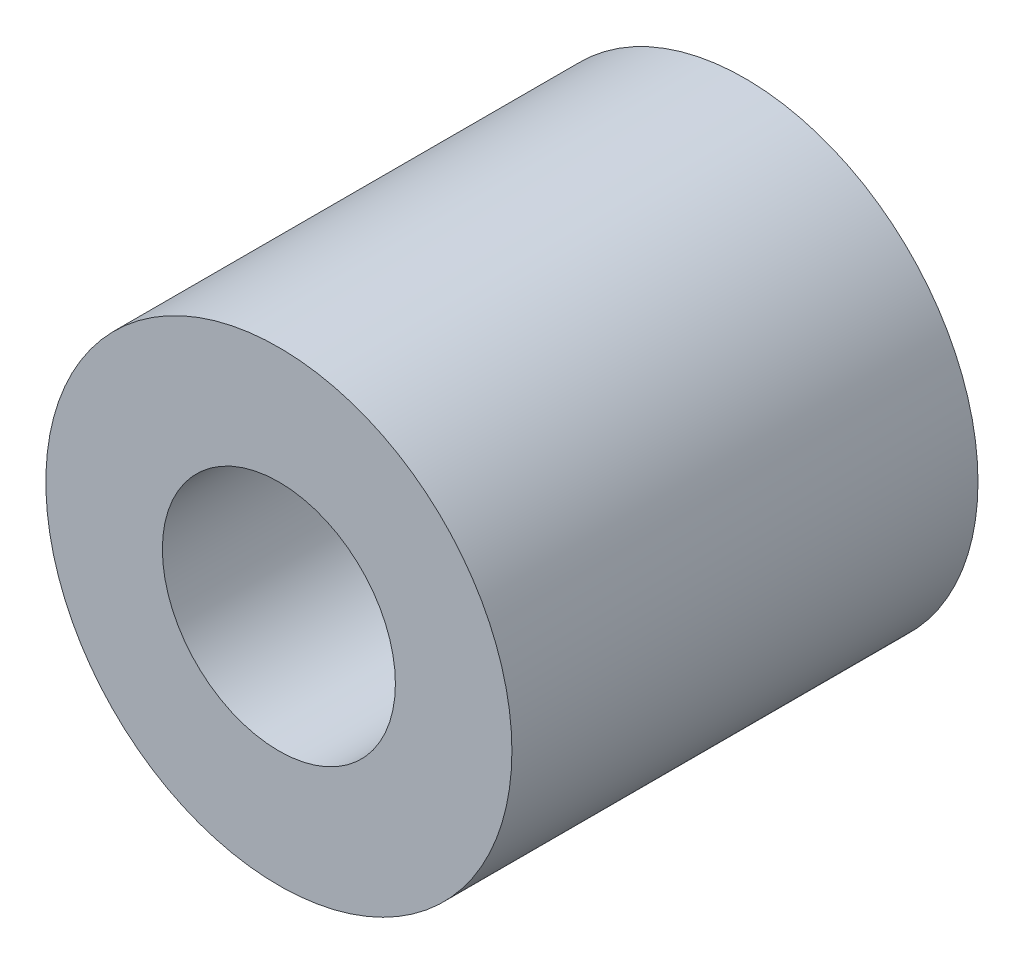
SolidWorks part; units mm, degrees
ref_plane "Front Plane" through (0, 0, 0) normal (0, 0, 1) x (1, 0, 0)
ref_plane "Top Plane" through (0, 0, 0) normal (0, 1, 0) x (1, 0, 0)
ref_plane "Right Plane" through (0, 0, 0) normal (1, 0, 0) x (0, 0, -1)
sketch "Sketch1" plane through (0, 0, 0) normal (0, 0, 1) x (1, 0, 0)
  circle A0 centre (0, 0) radius 2.5
  circle A1 centre (0, 0) radius 1.25
  dimension "D1" = 5
  dimension "D2" = 2.5
extrude "Boss-Extrude1" add sketch "Sketch1" along normal blind 5
